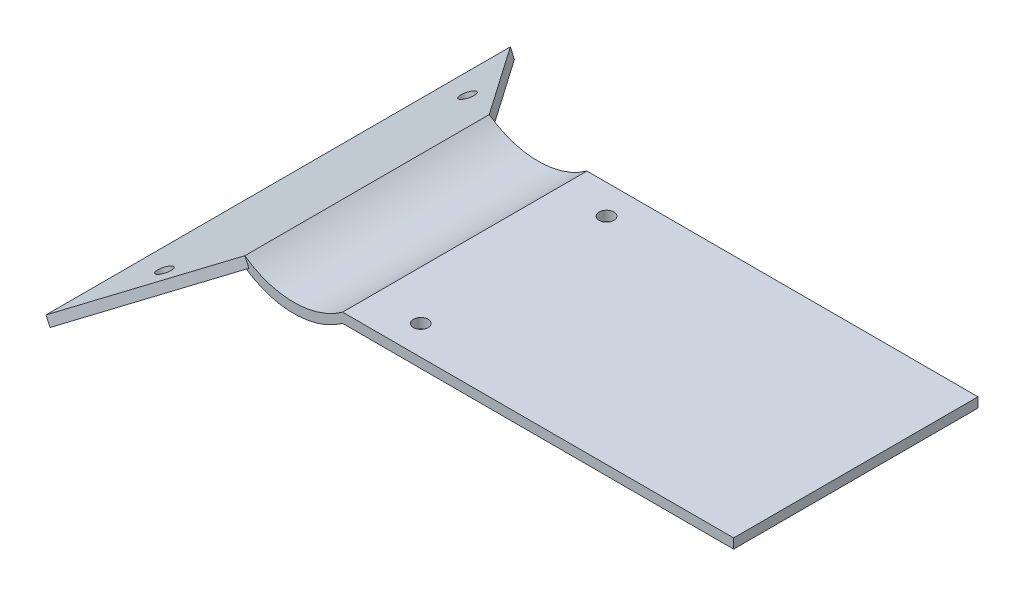
SolidWorks part; units mm, degrees
material "PBT 一般用途"
ref_plane "前视基准面" through (0, 0, 0) normal (0, 0, 1) x (1, 0, 0)
ref_plane "上视基准面" through (0, 0, 0) normal (0, 1, 0) x (1, 0, 0)
ref_plane "右视基准面" through (0, 0, 0) normal (1, 0, 0) x (0, 0, -1)
sketch "草图1" plane through (0, 0, 0) normal (0, 0, 1) x (1, 0, 0)
  line L0 (-600, 10) -> (-600, -10)
  line L1 (400, -10) -> (-400, -10)
  line L2 (400, -10) -> (400, 10)
  line L3 (400, 10) -> (-400, 10)
  line L4 (-400, -10) -> (-400, 10)
  line L5 (400, -10) -> (-400, 10) construction
  line L6 (400, 10) -> (-400, -10) construction
  line L7 (-600, -10) -> (-818.1742, -110)
  line L8 (-600, 10) -> (-781.8119, -73.3333)
  line L9 (-781.8119, -73.3333) -> (-818.1742, -110)
  arc A0 (-600, -10) -> (-400, -10) centre (-500, 127.4773) ccw
  arc A1 (-600, 10) -> (-400, 10) centre (-500, 147.4773) ccw
  point P0 (0, 0)
  dimension "D3" = 170
  dimension "D4" = 170
  dimension "D1" = 800
  dimension "D2" = 20
  dimension "D5" = 200
  dimension "D6" = 200
  dimension "D7" = 240
  dimension "D8" = 100
extrude "凸台-拉伸1" add sketch "草图1" along normal blind 500 contours L4 L1 L2 L3 | A1 L0 A0 L4 | L8 L9 L7 L0
sketch "草图3" plane through (-107.9544, 235.5287, 0) normal (-0.4167, 0.9091, 0) x (0.9091, 0.4167, 0)
  line L0 (-541.2689, 0) -> (-741.2689, 225)
  line L1 (-741.2689, 225) -> (-741.2689, 0)
  line L2 (-541.2689, -250) -> (-741.2689, -250) construction
  line L3 (-541.2689, -500) -> (-541.2689, 0) construction
  line L4 (-741.2689, -500) -> (-741.2689, 0) construction
  line L5 (-741.2689, -725) -> (-741.2689, -500)
  line L6 (-541.2689, -500) -> (-741.2689, -725)
  line L7 (-541.2689, 0) -> (-741.2689, 0) construction
  circle A0 centre (-656.2689, 60) radius 15
  circle A1 centre (-656.2689, -560) radius 15
  line M1 (-541.2689, 0) -> (-741.2689, 0)
  line M3 (-741.2689, -500) -> (-541.2689, -500)
  dimension "D1" = 85
  dimension "D5" = 30
  dimension "D2" = 60
  dimension "D3" = 225
extrude "凸台-拉伸2" add sketch "草图3" against normal blind 20 contours L6 L5 M3 | L0 L1 M1
sketch "草图4" plane through (0, 10, 0) normal (0, 1, 0) x (1, 0, 0)
  line L0 (400, -500) -> (-400, -500) construction
  line L1 (-175, -455) -> (-425, -455)
  line L2 (-175, -455) -> (-175, -425)
  line L3 (-175, -425) -> (-425, -425)
  line L4 (-425, -455) -> (-425, -425)
  line L5 (-175, -455) -> (-425, -425) construction
  line L6 (-175, -425) -> (-425, -455) construction
  line L7 (400, -500) -> (400, 0) construction
  line L8 (-400, -250) -> (-265.4126, -250) construction
  line L9 (-400, -500) -> (-400, 0) construction
  line L10 (-425, -45) -> (-425, -75)
  line L11 (-175, -45) -> (-425, -45)
  line L12 (-175, -45) -> (-175, -75)
  line L13 (-175, -75) -> (-425, -75)
  point P0 (-300, -440)
  dimension "D1" = 250
  dimension "D2" = 30
  dimension "D3" = 60
  dimension "D4" = 700
sketch "草图5" plane through (0, 10, 0) normal (0, 1, 0) x (1, 0, 0)
  line L0 (-400, -250) -> (-265.4126, -250)
  line L1 (400, 0) -> (-400, 0) construction
  line L2 (-400, -500) -> (-400, 0) construction
  circle A0 centre (-300, -60) radius 15
  circle A1 centre (-300, -440) radius 15
  dimension "D1" = 30
  dimension "D2" = 60
  dimension "D3" = 100
extrude "切除-拉伸1" cut sketch "草图5" against normal through all contours A0 | A1
